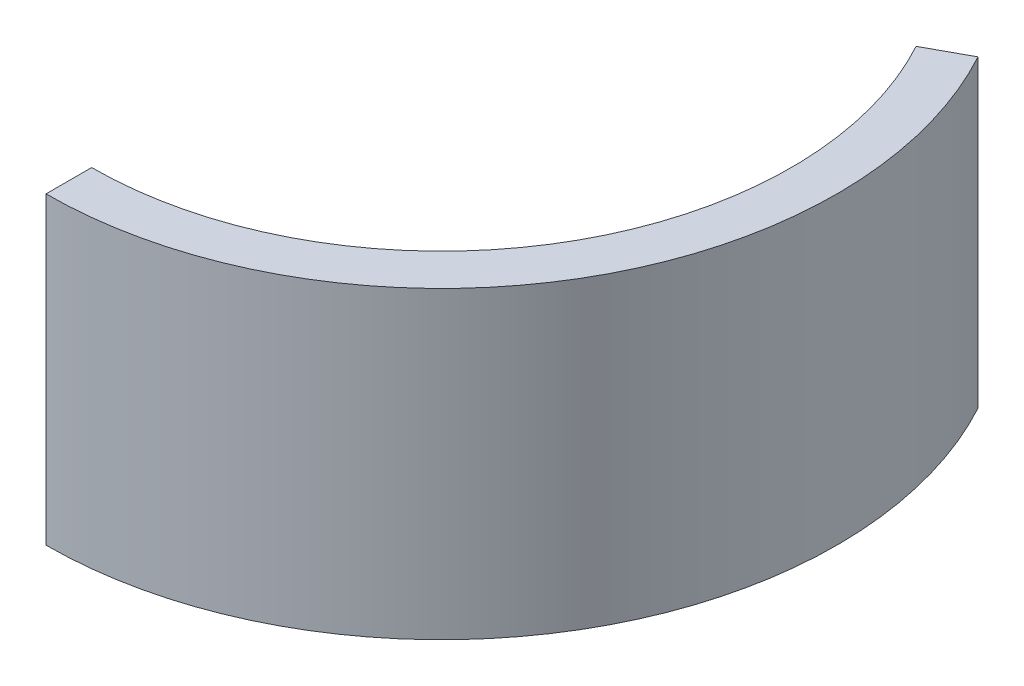
SolidWorks part; units mm, degrees
material "柔性聚氨酯泡沫体"
ref_plane "前视基准面" through (0, 0, 0) normal (0, 0, 1) x (1, 0, 0)
ref_plane "上视基准面" through (0, 0, 0) normal (0, 1, 0) x (1, 0, 0)
ref_plane "右视基准面" through (0, 0, 0) normal (1, 0, 0) x (0, 0, -1)
other "Configuration Table"
sketch "草图1" plane through (0, 0, 0) normal (0, 1, 0) x (1, 0, 0)
  line L0 (20.199, 11) -> (22.8337, 12.4348)
  line L1 (0, -23) -> (0, -26)
  circle A0 centre (0, 0) radius 26 construction
  circle A1 centre (0, 0) radius 23 construction
  arc A2 (20.199, 11) -> (0, -23) centre (0, 0) cw
  arc A3 (0, -26) -> (22.8337, 12.4348) centre (0, 0) ccw
  dimension "D1" = 46
  dimension "D2" = 52
  dimension "D3" = 34
extrude "凸台-拉伸1" add sketch "草图1" along normal blind 20 contours L1 A3 L0 A2
